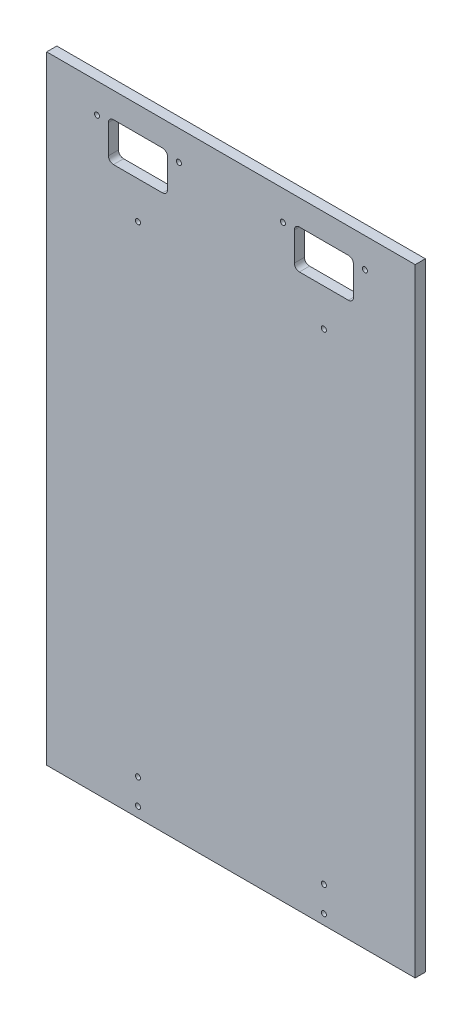
SolidWorks part; units mm, degrees
ref_plane "Спереди" through (0, 0, 0) normal (0, 0, 1) x (1, 0, 0)
ref_plane "Сверху" through (0, 0, 0) normal (0, 1, 0) x (1, 0, 0)
ref_plane "Справа" through (0, 0, 0) normal (1, 0, 0) x (0, 0, -1)
sketch "Эскиз1" plane through (0, 0, 0) normal (0, 0, 1) x (1, 0, 0)
  line L0 (-109, 326) -> (109, 326) construction
  line L4 (-109, 326) -> (109, 326)
  line L8 (0, 0) -> (0, 50000) construction
  line L9 (-55, -58.9588) -> (-55, -9.2224) construction
  line L10 (-70, -59) -> (-40, -59) construction
  line L11 (-55, 355.1773) -> (-55, 258.9299) construction
  line L12 (-40, 326) -> (-70, 326) construction
  line L13 (72.5, 288) -> (72.5, 311)
  line L14 (-37.5, 288) -> (-72.5, 288)
  line L15 (-37.5, 288) -> (-37.5, 311)
  line L16 (-37.5, 311) -> (-72.5, 311)
  line L17 (-72.5, 288) -> (-72.5, 311)
  line L18 (-37.5, 288) -> (-72.5, 311) construction
  line L19 (-37.5, 311) -> (-72.5, 288) construction
  line L20 (37.5, 311) -> (72.5, 311)
  line L21 (37.5, 288) -> (37.5, 311)
  line L22 (37.5, 288) -> (72.5, 288)
  line L23 (-109, 326) -> (-109.0001, -39.5)
  line L24 (-109.0001, -39.5) -> (109, -39.5)
  line L25 (109, -39.5) -> (109, 326)
  circle A0 centre (-55, -33.5) radius 1.5
  circle A1 centre (-55, -18.5) radius 1.5
  circle A2 centre (55, -18.5) radius 1.5
  circle A3 centre (55, -33.5) radius 1.5
  circle A4 centre (-79.25, 308.5) radius 1.5
  circle A5 centre (-55, 266) radius 1.5
  circle A6 centre (-30.75, 308.5) radius 1.5
  circle A7 centre (30.75, 308.5) radius 1.5
  circle A8 centre (55, 266) radius 1.5
  circle A9 centre (79.25, 308.5) radius 1.5
  point P4 (-55, -33.2719)
  point P19 (-55, -59)
  point P28 (-55, 326)
  point P30 (-55, 299.5)
  point P46 (55, 299.5)
  dimension "D1" = 3
  dimension "D7" = 3
  dimension "D3" = 15
  dimension "D4" = 35
  dimension "D5" = 23
  dimension "D6" = 15
  dimension "D8" = 17.5
  dimension "D9" = 60
  dimension "D10" = 48.5
  dimension "D2" = 365.5
  dimension "D11" = 6
extrude "Бобышка-Вытянуть1" add sketch "Эскиз1" along normal blind 6
fillet "Скругление1" radius 3 8 edges at (37.5, 288, 3) (72.5, 288, 3) (72.5, 311, 3) (37.5, 311, 3) (-72.5, 311, 3) (-37.5, 311, 3) (-37.5, 288, 3) (-72.5, 288, 3)
equation "\"D5@Эскиз1\"=15+8"
